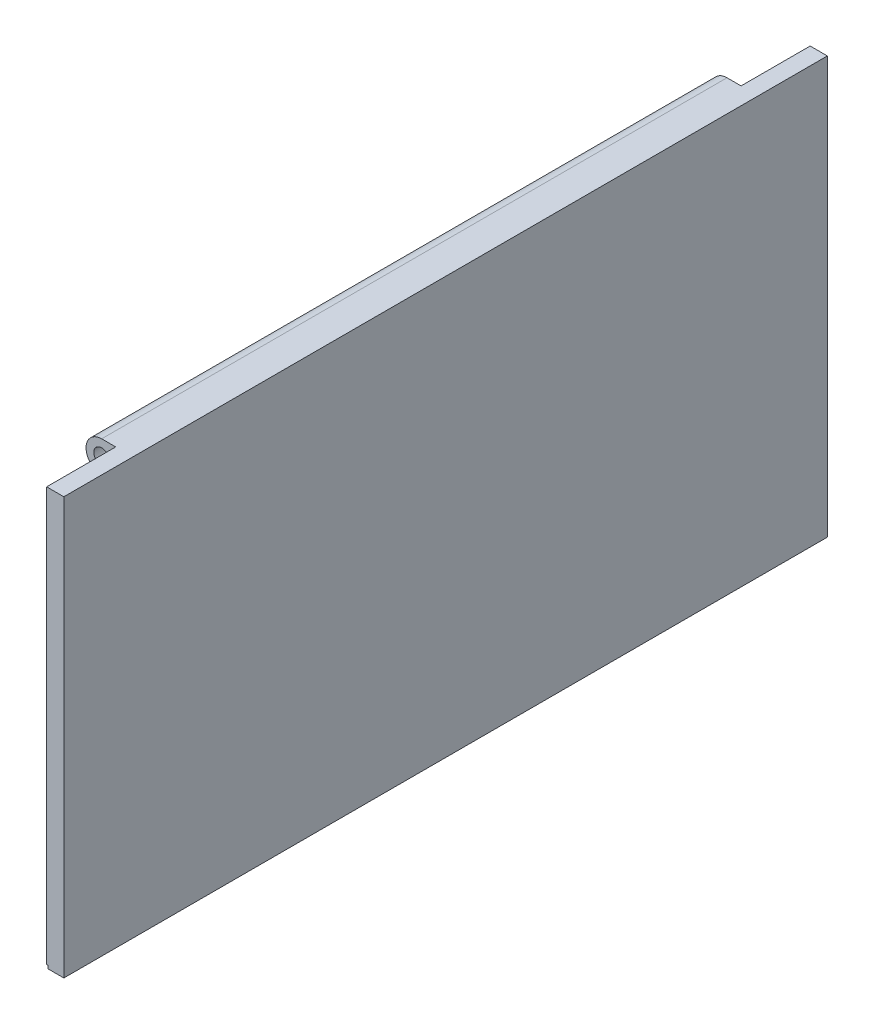
SolidWorks part; units mm, degrees
ref_plane "Piano frontale" through (0, 0, 0) normal (0, 0, 1) x (1, 0, 0)
ref_plane "Piano superiore" through (0, 0, 0) normal (0, 1, 0) x (1, 0, 0)
ref_plane "Piano destro" through (0, 0, 0) normal (1, 0, 0) x (0, 0, -1)
sketch "Schizzo4" plane through (0, 0, 0) normal (0, 0, 1) x (1, 0, 0)
  circle A0 centre (0, 0) radius 2.5
  circle A1 centre (0, 0) radius 1.25
  dimension "D1" = 2.5
  dimension "D2" = 5
extrude "Estrusione-Estrusione3" add sketch "Schizzo4" along normal blind 100
ref_plane "Piano1" through (0, 0, 50) normal (0, 0, 1) x (1, 0, 0)
sketch "Schizzo5" plane through (0, 0, 50) normal (0, 0, 1) x (1, 0, 0)
  line L0 (0, 2.5) -> (5, 2.5)
  line L1 (5, 2.5) -> (5, -64.15)
  line L2 (0, -2.5) -> (2.5, -2.5)
  line L3 (2.5, -2.5) -> (2.5, -64.15)
  line L4 (2.5, -64.15) -> (5, -64.15)
  circle A0 centre (0, 0) radius 2.5 construction
  arc A1 (0, -2.5) -> (0, 2.5) centre (0, 0) ccw
  dimension "D1" = 66.65
  dimension "D2" = 5
  dimension "D3" = 0
extrude "Estrusione-Estrusione4" add sketch "Schizzo5" along normal mid plane 122.1
sketch "Schizzo6" plane through (0, 0, 0) normal (0, 0, -1) x (-1, 0, 0)
  line L1 (-2.5, -2.5) -> (5.737, -2.5)
  line L2 (-2.5, -2.5) -> (-2.5, 3.4704)
  line L3 (-2.5, 3.4704) -> (5.737, 3.4704)
  line L4 (5.737, -2.5) -> (5.737, 3.4704)
extrude "Taglio-Estrusione2" cut sketch "Schizzo6" along normal blind 119.1
sketch "Schizzo7" plane through (0, 0, 100) normal (0, 0, 1) x (1, 0, 0)
  line L1 (2.5, -2.5) -> (-3.5147, -2.5)
  line L2 (2.5, -2.5) -> (2.5, 3.1743)
  line L3 (2.5, 3.1743) -> (-3.5147, 3.1743)
  line L4 (-3.5147, -2.5) -> (-3.5147, 3.1743)
extrude "Taglio-Estrusione3" cut sketch "Schizzo7" along normal blind 119.1
sketch "Schizzo8" plane through (0, 0, 111.05) normal (0, 0, 1) x (1, 0, 0)
  line L0 (2.5, 2.5) -> (2.5, -64.15) construction
  line L1 (5, 2.5) -> (2.25, 2.5)
  line L2 (5, 2.5) -> (5, -63.65)
  line L3 (5, -63.65) -> (2.25, -63.65)
  line L4 (2.25, 2.5) -> (2.25, -63.65)
  dimension "D1" = 0.25
extrude "Estrusione-Estrusione5" add sketch "Schizzo8" against normal up to surface (122.1 mm away) up to face at (3.75, -30.825, -11.05)
sketch "Schizzo9" plane through (0, 0, 100) normal (0, 0, 1) x (1, 0, 0)
  line L0 (2.25, -2.5) -> (2.25, -1.8839)
  line L1 (2.25, 2.5) -> (2.25, -63.65) construction
  line L2 (2.25, -1.8839) -> (1.6198, -2.5)
  line L3 (0, -2.5) -> (2.25, -2.5) construction
  line L4 (1.6198, -2.5) -> (2.25, -2.5)
extrude "Taglio-Estrusione4" cut sketch "Schizzo9" against normal blind 300
fillet "Raccordo1" radius 2 1 edges at (1.6198, -2.5, 50)
